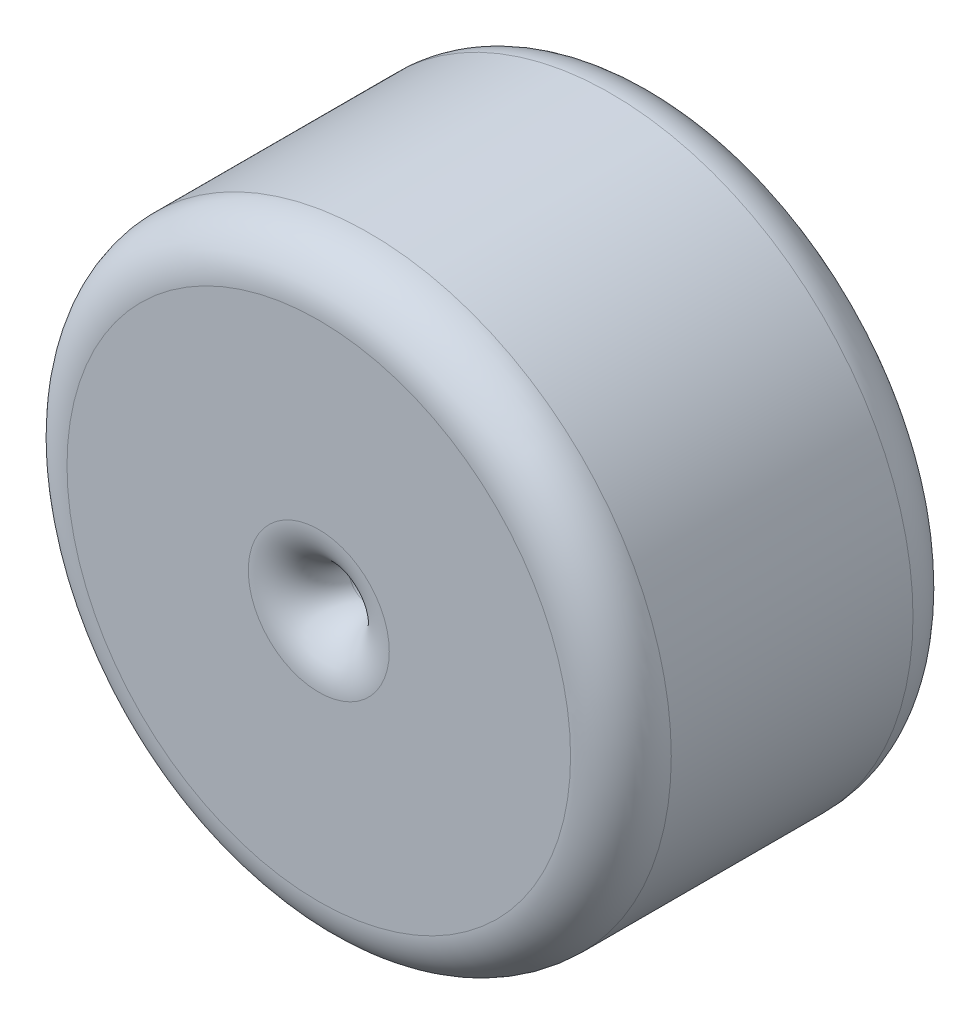
SolidWorks part; units mm, degrees
ref_plane "Front Plane" through (0, 0, 0) normal (0, 0, 1) x (1, 0, 0)
ref_plane "Top Plane" through (0, 0, 0) normal (0, 1, 0) x (1, 0, 0)
ref_plane "Right Plane" through (0, 0, 0) normal (1, 0, 0) x (0, 0, -1)
sketch "Sketch1" plane through (0, 0, 0) normal (0, 0, 1) x (1, 0, 0)
  circle A0 centre (0, 0) radius 15
  circle A1 centre (0, 0) radius 1
extrude "Boss-Extrude1" add sketch "Sketch1" along normal blind 17 contours A0
sketch "Sketch2" plane through (0, 0, 0) normal (0, 0, -1) x (-1, 0, 0)
  circle A0 centre (0, 0) radius 1
extrude "Cut-Extrude1" cut sketch "Sketch2" against normal blind 17
fillet "Fillet3" radius 2.5 3 edges at (-1, 0, 17) (15, 0, 0) (15, 0, 17)
equation "\"0.25.00cm\"=1"
